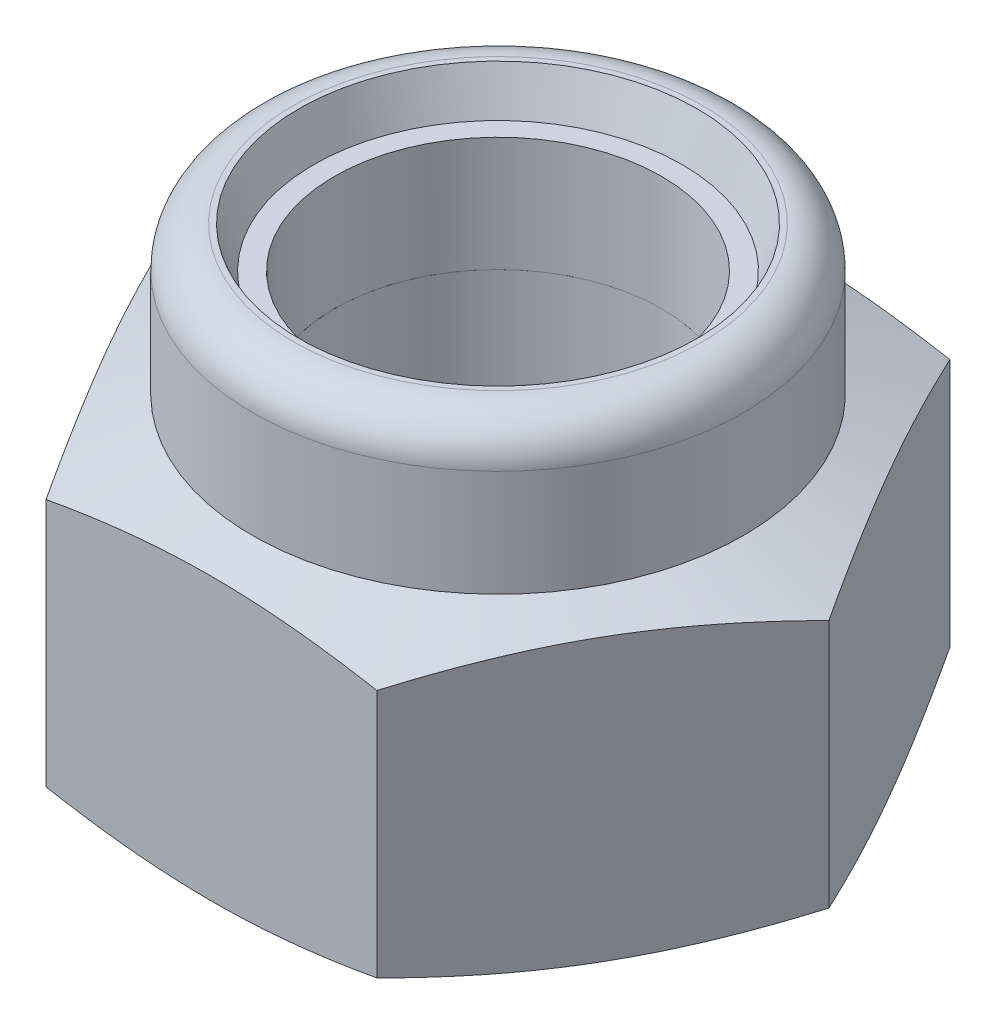
SolidWorks part; units mm, degrees
material "AISI 304"
ref_plane "前视基准面" through (0, 0, 0) normal (0, 0, 1) x (1, 0, 0)
ref_plane "上视基准面" through (0, 0, 0) normal (0, 1, 0) x (1, 0, 0)
ref_plane "右视基准面" through (0, 0, 0) normal (1, 0, 0) x (0, 0, -1)
other "Configuration Table"
sketch "草图1" plane through (0, 0, 0) normal (0, 0, 1) x (1, 0, 0)
  line L0 (0, -0.0416) -> (0, 2990.141) construction
  line L1 (2, 3.7) -> (2, 0.1732)
  line L2 (2, 0.1732) -> (2.3, 0)
  line L3 (2.3, 0) -> (3, 0)
  line L4 (3, 0) -> (3, 5.1)
  line L5 (2.5, 5.6) -> (2.432, 5.6)
  line L6 (2.432, 5.6) -> (2.25, 5.1)
  line L8 (2, 3.7) -> (2.5, 3.7)
  line L9 (2.5, 3.7) -> (2.5, 5.1)
  line L10 (2.5, 5.1) -> (2.25, 5.1)
  arc A0 (3, 5.1) -> (2.5, 5.6) centre (2.5, 5.1) ccw
  point P18 (2.25, 3.7)
  dimension "a" = 0.5
  dimension "D" = 4
  dimension "dw" = 6
  dimension "m" = 3.7
  dimension "da" = 4.6
  dimension "theta" = 60
  dimension "h" = 5.6
  dimension "t" = 0.5
  dimension "hj" = 0.5
  dimension "D10" = 70
revolve "旋转1" add sketch "草图1" angle 360 about L0
sketch "草图2" plane through (0, 0, 0) normal (0, 1, 0) x (1, 0, 0)
  line L1 (4.0415, 0) -> (2.0207, 3.5)
  line L2 (2.0207, 3.5) -> (-2.0207, 3.5)
  line L3 (-2.0207, 3.5) -> (-4.0415, 0)
  line L4 (-4.0415, 0) -> (-2.0207, -3.5)
  line L5 (-2.0207, -3.5) -> (2.0207, -3.5)
  line L6 (2.0207, -3.5) -> (4.0415, 0)
  circle A0 centre (0, 0) radius 3 construction
  circle A1 centre (0, 0) radius 3 construction
  circle A2 centre (0, 0) radius 2.5
  circle A3 centre (0, 0) radius 2.5 construction
  dimension "s" = 7
extrude "凸台-拉伸1" add sketch "草图2" along normal blind 3.8
sketch "草图3" plane through (0, 0, 0) normal (0, 0, 1) x (1, 0, 0)
  line L0 (-3, 3.8) -> (-4.0415, 3.4209)
  line L1 (-4.0415, 3.8) -> (-4.0415, 0) construction
  line L2 (-4.0415, 3.4209) -> (-4.0415, 3.8)
  line L3 (-4.0415, 3.8) -> (-3, 3.8)
  line L4 (-3, 0) -> (-4.0415, 0)
  line L5 (-4.0415, 0) -> (-2.0207, 0) construction
  line L6 (-4.0415, 0) -> (-4.0415, 0.3791)
  line L7 (-4.0415, 0.3791) -> (-3, 0)
  line L8 (0, 0) -> (0, 50000) construction
  dimension "D1" = 20
revolve "切除-旋转1" cut sketch "草图3" angle 360 about L8
sketch "草图4" plane through (0, 3.7, 0) normal (0, 1, 0) x (1, 0, 0)
  circle A0 centre (0, 0) radius 2
  circle A1 centre (0, 0) radius 2.5
  circle A2 centre (0, 0) radius 2.5 construction
  circle A3 centre (0, 0) radius 2 construction
extrude "凸台-拉伸2" add sketch "草图4" along normal up to surface (1.4 mm away) separate body up to face at (0, 5.1, -2.5)
